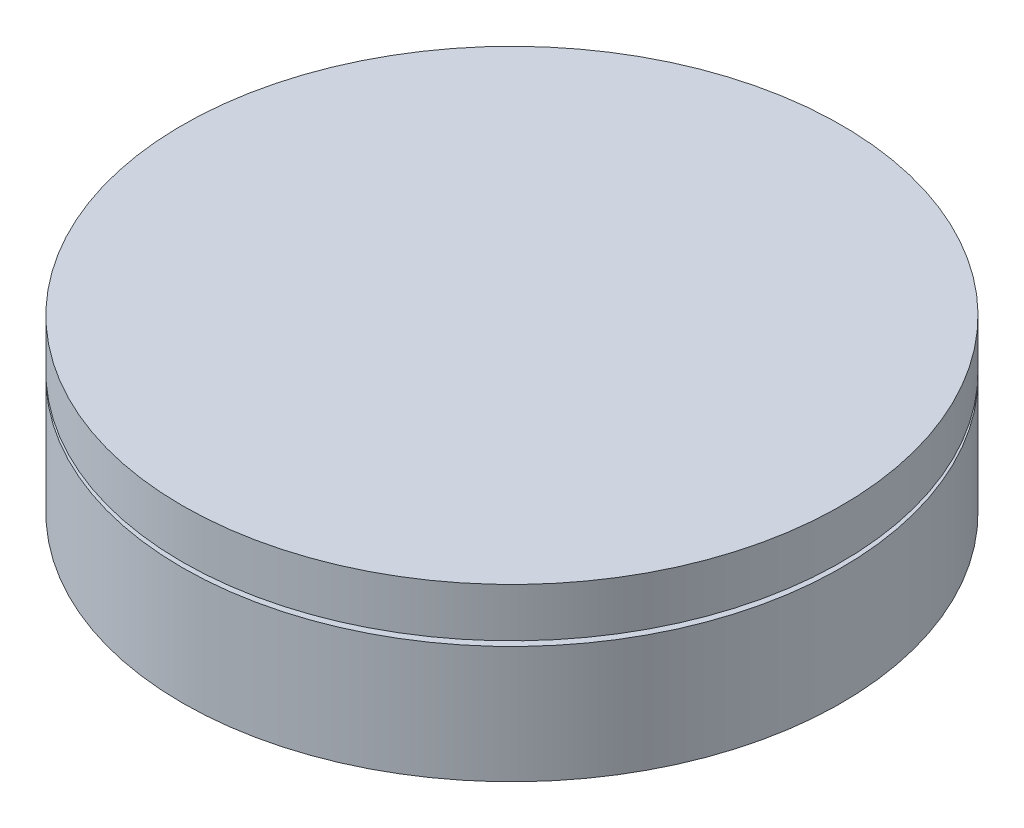
SolidWorks part; units mm, degrees
ref_plane "Front Plane" through (0, 0, 0) normal (0, 0, 1) x (1, 0, 0)
ref_plane "Top Plane" through (0, 0, 0) normal (0, 1, 0) x (1, 0, 0)
ref_plane "Right Plane" through (0, 0, 0) normal (1, 0, 0) x (0, 0, -1)
sketch "Sketch1" plane through (0, 0, 0) normal (0, 1, 0) x (1, 0, 0)
  circle A0 centre (0, 0) radius 67.5
  dimension "D1" = 135
extrude "Boss-Extrude1" add sketch "Sketch1" along normal blind 35
sketch "Sketch2" plane through (0, 35, 0) normal (0, 1, 0) x (1, 0, 0)
  circle A0 centre (0, 0) radius 47.5
  circle A1 centre (0, 0) radius 67.5
  circle A2 centre (0, 0) radius 67.5
  dimension "D1" = 0
  dimension "D2" = 20
extrude "Cut-Extrude1" cut sketch "Sketch2" against normal blind 1 from offset 10 offset against normal yes
